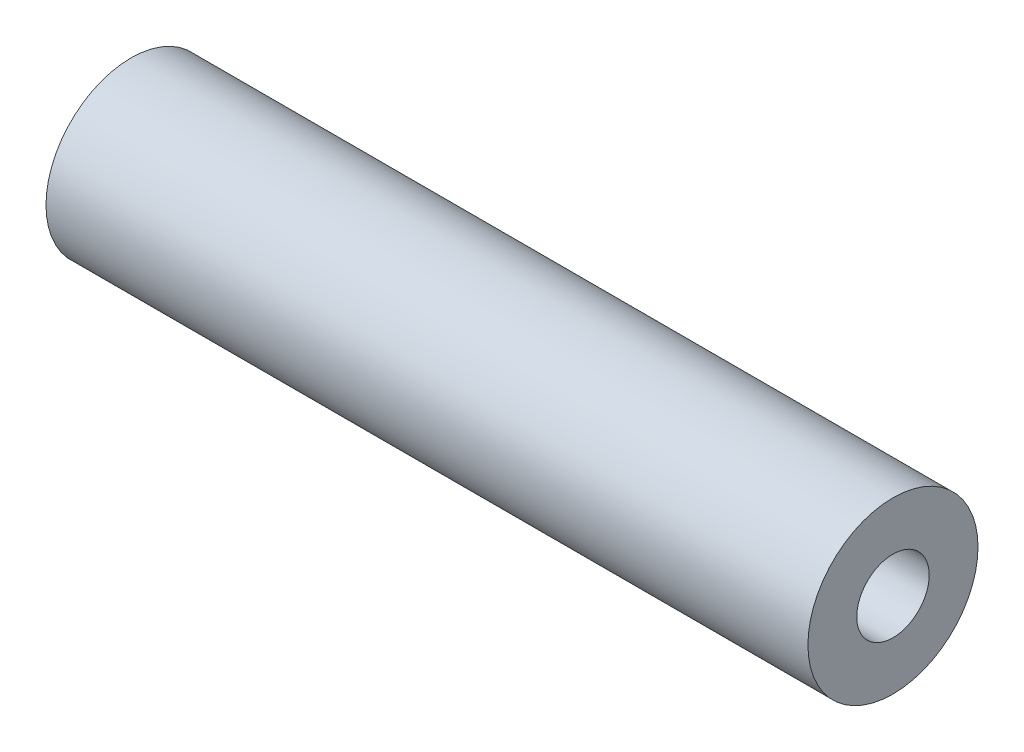
SolidWorks part; units mm, degrees
material "6061-T6 (SS)"
ref_plane "Front Plane" through (0, 0, 0) normal (0, 0, 1) x (1, 0, 0)
ref_plane "Top Plane" through (0, 0, 0) normal (0, 1, 0) x (1, 0, 0)
ref_plane "Right Plane" through (0, 0, 0) normal (1, 0, 0) x (0, 0, -1)
sketch "Sketch1" plane through (0, 0, 0) normal (1, 0, 0) x (0, 0, -1)
  circle A0 centre (0, 0) radius 3.175
  dimension "D2" = 6.35
extrude "Boss-Extrude1" add sketch "Sketch1" along normal blind 28.448
hole_wizard "#6-32 Tapped Hole1" positions "Sketch3" profile "Sketch4" tap size "#6-32" standard "ANSI Inch" end condition through all
sketch "Sketch3" plane through (28.448, 0, 0) normal (1, 0, 0) x (0, 0, -1)
  point P0 (0, 0)
sketch "Sketch4" plane through (28.448, 0, 0) normal (0, 1, 0) x (0, 0, -1)
  line L0 (0, 0) -> (0, 28.448)
  line L1 (0, 28.448) -> (1.3525, 28.448)
  line L2 (1.3525, 28.448) -> (1.3525, 0)
  line L5 (1.3525, 0) -> (0, 0)
  line L11 (0, -6.35) -> (0, 107.95) construction
  dimension "Thru Tap Drill Dia." = 2.7051
  dimension "Thru Tap Drill Depth" = 28.448
cosmetic thread "Hole Thread1" parameters "D2"=3.5052
